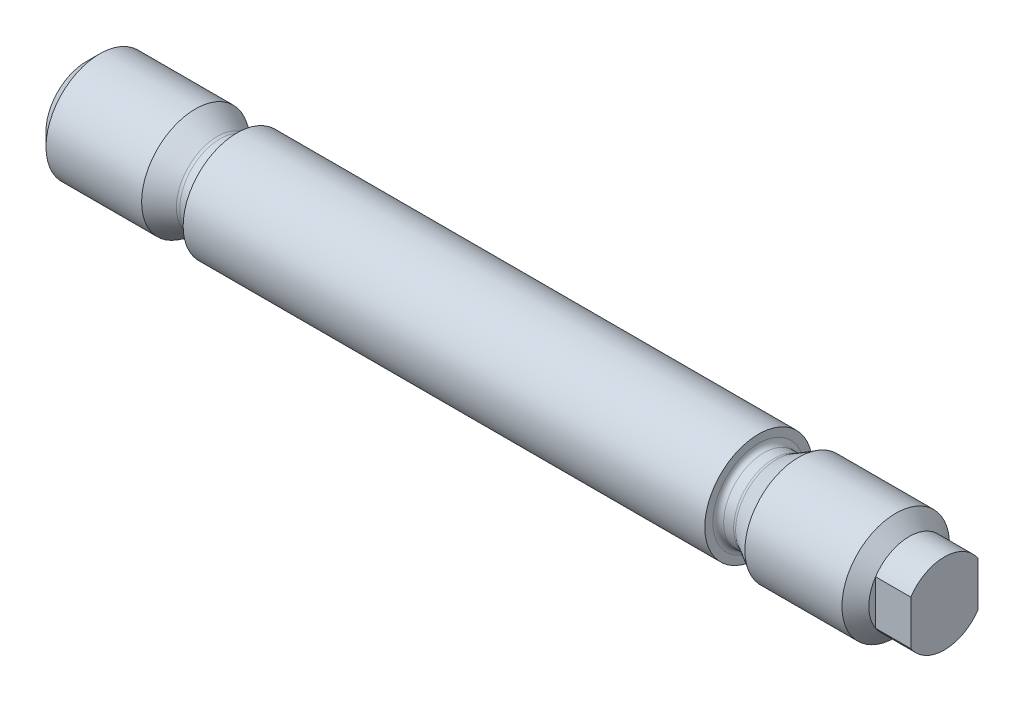
SolidWorks part; units mm, degrees
revolve "BaseBody" add sketch "BodySke" angle 360 about L14
sketch "BodySke" plane through (0, 0, 0) normal (0, 0, 1) x (1, 0, 0)
  line L0 (19.5, 6.1072) -> (16.2215, 8)
  line L1 (16.2215, 8) -> (2, 8)
  line L2 (22.4, 8) -> (22.4, 6.8)
  line L3 (21.6, 6) -> (19.9, 6)
  line L5 (2, 8) -> (0, 6)
  line L7 (100, 8) -> (100, 6.8)
  line L8 (100.8, 6) -> (102.2856, 6)
  line L9 (102.6856, 6.1072) -> (105.9641, 8)
  line L10 (105.9641, 8) -> (120.4, 8)
  line L11 (120.4, 8) -> (122.4, 6)
  line L12 (122.4, 6) -> (122.4, 0)
  line L13 (122.4, 0) -> (0, 0)
  line L14 (-3.175, 0) -> (101.6, 0) construction
  line L15 (108.7794, -6) -> (122.4, -6) construction
  line L16 (100, -6) -> (102.5, -6) construction
  line L17 (37.0699, -8) -> (100, -8) construction
  line L18 (0, 6) -> (0, 0)
  line L19 (22.4, 8) -> (100, 8)
  line L20 (104.5, 10.8514) -> (104.5, -6.5014) construction
  line L21 (100, 10.2761) -> (100, -5.5735) construction
  arc A0 (19.9, 6) -> (19.5, 6.1072) centre (19.9, 6.8) cw
  arc A1 (22.4, 6.8) -> (21.6, 6) centre (21.6, 6.8) cw
  arc A2 (102.2856, 6) -> (102.6856, 6.1072) centre (102.2856, 6.8) ccw
  arc A3 (100, 6.8) -> (100.8, 6) centre (100.8, 6.8) ccw
  point P26 (102.5, 6)
  point P29 (100, 6)
  dimension "Thread_neck_width" = 2.5
  dimension "Thread_nom" = 22.4
  dimension "Advance" = 2
  dimension "Thread_lim" = 17.9
  dimension "Shoulder_neck_width" = 2.5
  dimension "Studend_length" = 22.4
  dimension "Length" = 100
  dimension "Thread_len" = 22.4
cosmetic thread "ThreadCosmetic" [suppressed] parameters "Thread_minor"=12
cosmetic thread "ThreadCosmeticStud" [suppressed] parameters "Thrd_Minor"=12
ref_plane "Plane1" through (0, 0, 0) normal (0, 0, 1) x (1, 0, 0)
ref_plane "Plane2" through (0, 0, 0) normal (0, 1, 0) x (1, 0, 0)
ref_plane "Plane3" through (0, 0, 0) normal (1, 0, 0) x (0, 0, -1)
sketch "ThdSchSke" plane through (0, 0, 0) normal (0, 0, 1) x (1, 0, 0)
  line L0 (104.5, -6) -> (103.0996, -8)
  line L1 (104.5, -6) -> (105.9004, -8)
  line L2 (105.9004, -8) -> (105.9004, -10)
  line L3 (-3.175, 0) -> (5.1513, 0) construction
  line L5 (105.9004, -10) -> (103.0996, -10)
  line L6 (103.0996, -10) -> (103.0996, -8)
  line L7 (122.4, -6) -> (122.4, 6) construction
  dimension "Thread_minor" = 12
  dimension "Diameter" = 16
  dimension "Start" = 17.9
  dimension "SideAngle" = 55
  dimension "VeeAngle" = 70
  dimension "Overcut" = 20
revolve "ThreadSchematic" [suppressed] cut sketch "ThdSchSke" angle 360 about L3
pattern_linear "ThdSchPat" [suppressed]
sketch "ThdSchSketStud" plane through (0, 0, 0) normal (0, 0, 1) x (1, 0, 0)
  line L0 (17.9, -6) -> (16.4996, -8)
  line L1 (17.9, -6) -> (19.3004, -8)
  line L2 (19.3004, -8) -> (19.3004, -10)
  line L3 (-3.175, 0) -> (5.1513, 0) construction
  line L5 (19.3004, -10) -> (16.4996, -10)
  line L6 (16.4996, -10) -> (16.4996, -8)
  line L7 (0, 6) -> (0, -6) construction
  dimension "Thread_minor" = 12
  dimension "Diameter" = 16
  dimension "SideAngle" = 55
  dimension "VeeAngle" = 70
  dimension "Overcut" = 20
revolve "ThreadSchematicStud" [suppressed] cut sketch "ThdSchSketStud" angle 360 about L3
pattern_linear "ThdSchPatStud" [suppressed]
sketch "DogPointSke" plane through (122.4, 0, 0) normal (1, 0, 0) x (0, 0, -1)
  line L0 (-5, 3.3166) -> (-5, -3.3166)
  line L1 (5, 3.3166) -> (5, -3.3166)
  line L2 (0, -9.525) -> (0, 9.525) construction
  arc A0 (-5, -3.3166) -> (5, -3.3166) centre (0, 0) ccw
  arc A2 (5, 3.3166) -> (-5, 3.3166) centre (0, 0) ccw
  dimension "Point_Dia" = 12
  dimension "Dog_Width" = 10
extrude "DogPoint" add sketch "DogPointSke" along normal blind 5.24
equation "\"Thread_len@BodySke\" = \"Thread_nom@BodySke\""
equation "\"Studend_length@BodySke\" = \"Thread_len@BodySke\""
equation "\"Thread_minor@ThreadCosmetic\" = \"Minor_dia@BodySke\""
equation "\"Thrd_Minor@ThreadCosmeticStud\" = \"Thread_minor@ThreadCosmetic\""
equation "\"Thread_minor@ThdSchSke\" = \"Minor_dia@BodySke\""
equation "\"Diameter@ThdSchSke\" = \"Thread_dia@BodySke\""
equation "\"Overcut@ThdSchSke\" = \"Thread_dia@BodySke\" * 1.25"
equation "\"Start@ThdSchSke\" = \"Thread_nom@BodySke\"  - \"Thread_neck_width@BodySke\" - \"Advance@BodySke\""
equation "\"Num_threads@ThdSchPat\" = int( \"Start@ThdSchSke\" / \"Advance@BodySke\" + 0.999 ) + 1"
equation "\"Advance@ThdSchPat\" = \"Start@ThdSchSke\" /  ( \"Num_threads@ThdSchPat\" - 1 ) 'relax it"
equation "'  \"Num_threads@ThdSchPat\" = \"Num_threads@ThdSchPat\" - sgn( \"Num_threads@ThdSchPat\" - 1 ) '---chamfered tips only---"
equation "\"Diameter@ThdSchSketStud\" = \"Diameter@ThdSchSke\""
equation "\"Thread_minor@ThdSchSketStud\" = \"Thread_minor@ThdSchSke\""
equation "\"Overcut@ThdSchSketStud\" = \"Overcut@ThdSchSke\""
equation "\"Start_@ThdSchSketStud\" = \"Studend_length@BodySke\" - \"Shoulder_neck_width@BodySke\" - \"Advance@BodySke\""
equation "\"Num_Threads@ThdSchPatStud\" = int ( \"Start_@ThdSchSketStud\" / \"Advance@BodySke\" + 0.999 )  + 1"
equation "\"Advance@ThdSchPatStud\" = \"Start_@ThdSchSketStud\" /  ( \"Num_Threads@ThdSchPatStud\" - 1 ) 'relax it"
